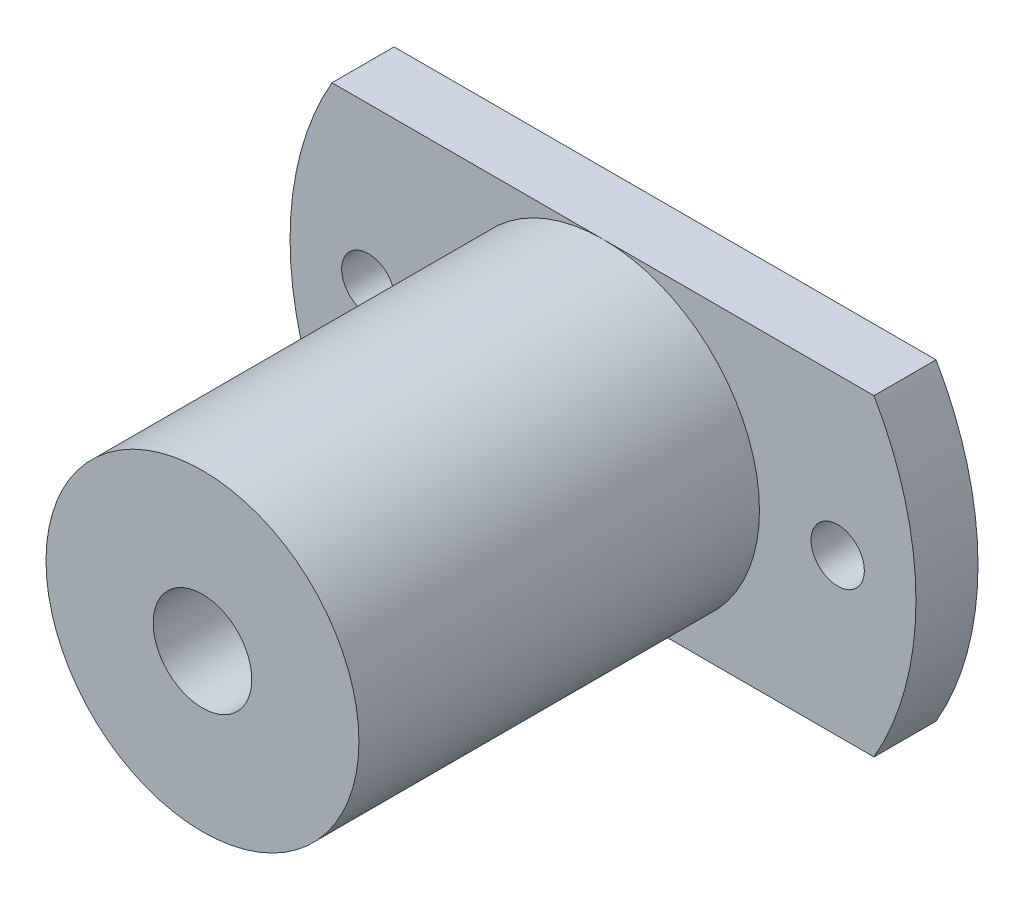
SolidWorks part; units mm, degrees
ref_plane "Front Plane" through (0, 0, 0) normal (0, 0, 1) x (1, 0, 0)
ref_plane "Top Plane" through (0, 0, 0) normal (0, 1, 0) x (1, 0, 0)
ref_plane "Right Plane" through (0, 0, 0) normal (1, 0, 0) x (0, 0, -1)
sketch "Sketch1" plane through (0, 0, 0) normal (0, 0, 1) x (1, 0, 0)
  circle A0 centre (0, 0) radius 15.875
  dimension "D1" = 31.75
extrude "Boss-Extrude1" add sketch "Sketch1" along normal blind 23.4696
sketch "Sketch2" plane through (0, 0, 23.4696) normal (0, 0, 1) x (1, 0, 0)
  circle A0 centre (0, 0) radius 7.9375
  circle A1 centre (0, 0) radius 15.875 construction
  circle A2 centre (0, 0) radius 15.875
  dimension "D1" = 15.875
extrude "Cut-Extrude1" cut sketch "Sketch2" against normal blind 20.32
hole_wizard "M6x1.0 Tapped Hole1" positions "Sketch4" profile "Sketch3" tap size "M6x1.0" standard "ANSI Metric" end condition through all
sketch "Sketch4" plane through (0, 0, 23.4696) normal (0, 0, 1) x (1, 0, 0)
  point P0 (0, 0)
sketch "Sketch3" plane through (0, 0, 23.4696) normal (1, 0, 0) x (0, -1, 0)
  line L0 (0, 0) -> (0, 23.4696)
  line L1 (0, 23.4696) -> (2.5, 23.4696)
  line L2 (2.5, 23.4696) -> (2.5, 0)
  line L5 (2.5, 0) -> (0, 0)
  line L11 (0, -6.35) -> (0, 107.95) construction
  dimension "Thru Tap Drill Dia." = 5
  dimension "Thru Tap Drill Depth" = 23.4696
cosmetic thread "Hole Thread1" parameters "D2"=6
sketch "Sketch5" plane through (0, 0, 3.1496) normal (0, 0, 1) x (1, 0, 0)
  circle A0 centre (0, 0) radius 11.9062 construction
  circle A1 centre (0, 0) radius 7.9375 construction
  point P6 (11.9062, 0)
  point P9 (0, 0)
  point P11 (-11.9062, 0)
  dimension "D1" = 23.8125
hole_wizard "#36 (0.1065) Diameter Hole2" positions "Sketch7" profile "Sketch6" hole size "#36" standard "ANSI Inch"
sketch "Sketch7" plane through (0, 0, 3.1496) normal (0, 0, 1) x (1, 0, 0)
  point P9 (11.9062, 0)
  point P12 (-11.9062, 0)
sketch "Sketch6" plane through (11.9062, 0, 3.1496) normal (1, 0, 0) x (0, -1, 0)
  line L0 (0, 0) -> (0, 7.1627)
  line L1 (0, 7.1627) -> (1.3525, 6.35)
  line L2 (1.3525, 6.35) -> (1.3525, 0)
  line L5 (1.3525, 0) -> (0, 0)
  line L10 (0, 7.1627) -> (-1.3525, 6.35) construction
  line L11 (0, -6.35) -> (0, 107.95) construction
  dimension "Hole Dia." = 2.7051
  dimension "Hole Depth" = 6.35
  dimension "Drill Angle" = 118
sketch "Sketch8" plane through (0, 0, 3.1496) normal (0, 0, 1) x (1, 0, 0)
  line L0 (0, 7.9375) -> (-13.7482, 7.9375)
  line L1 (0, 7.9375) -> (13.7482, 7.9375)
  line L2 (-13.7482, -7.9375) -> (13.7482, -7.9375)
  line L3 (0, 7.9375) -> (0, 0) construction
  circle A0 centre (0, 0) radius 7.9375 construction
  circle A1 centre (0, 0) radius 15.875 construction
  arc A2 (-13.7482, -7.9375) -> (13.7482, -7.9375) centre (0, 0) ccw
  arc A3 (13.7482, 7.9375) -> (-13.7482, 7.9375) centre (0, 0) ccw
extrude "Cut-Extrude2" cut sketch "Sketch8" against normal through all
